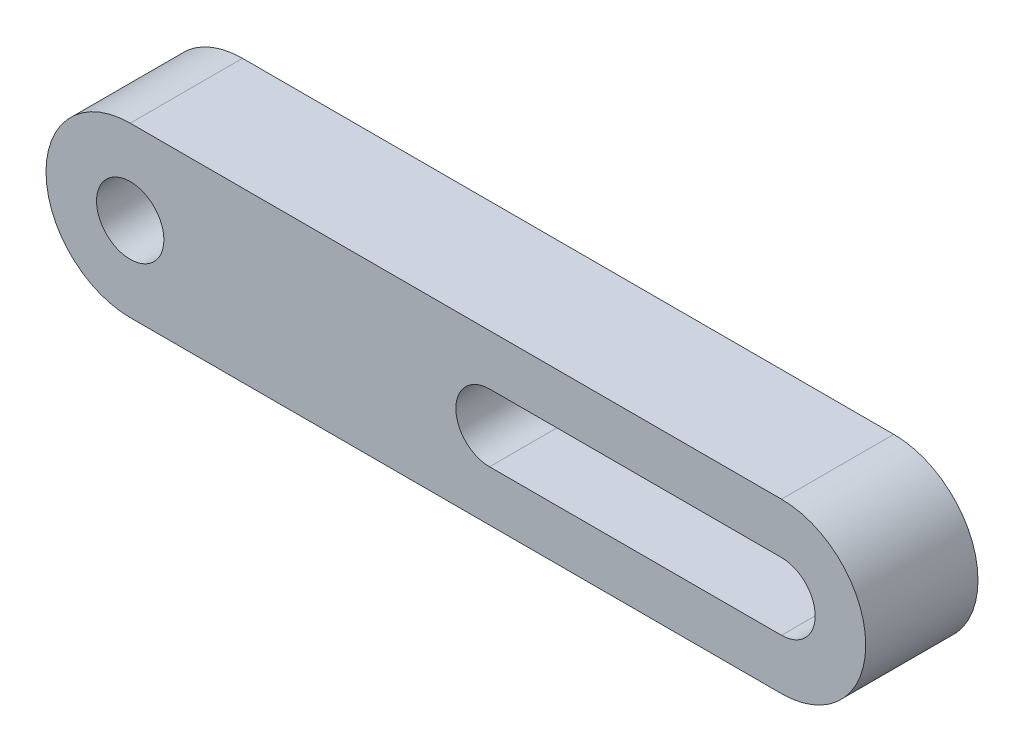
SolidWorks part; units mm, degrees
ref_plane "Alzado" through (0, 0, 0) normal (0, 0, 1) x (1, 0, 0)
ref_plane "Planta" through (0, 0, 0) normal (0, 1, 0) x (1, 0, 0)
ref_plane "Vista lateral" through (0, 0, 0) normal (1, 0, 0) x (0, 0, -1)
sketch "Croquis1" plane through (0, 0, 0) normal (0, 0, 1) x (1, 0, 0)
  line L0 (0, 0) -> (29, 0) construction
  line L1 (0, 3.75) -> (29, 3.75)
  line L2 (0, -3.75) -> (29, -3.75)
  line L3 (29, 0) -> (16, 0) construction
  line L4 (29, -1.5) -> (16, -1.5)
  line L5 (29, 1.5) -> (16, 1.5)
  line L6 (16, 1.5) -> (16, -1.5) construction
  arc A0 (0, 3.75) -> (0, -3.75) centre (0, 0) ccw
  arc A1 (29, -3.75) -> (29, 3.75) centre (29, 0) ccw
  circle A2 centre (0, 0) radius 1.5
  arc A4 (29, -1.5) -> (29, 1.5) centre (29, 0) ccw
  arc A5 (16, 1.5) -> (16, -1.5) centre (16, 0) ccw
  point P3 (14.5, 0)
  point P12 (22.5, 0)
  dimension "D3" = 3
  dimension "D4" = 1.5
  dimension "D1" = 13
  dimension "D2" = 7.5
  dimension "D5" = 16
extrude "Saliente-Extruir1" add sketch "Croquis1" along normal blind 5
ref_plane "Plano1" through (0, 0, 2.5) normal (0, 0, 1) x (1, 0, 0)
sketch "Croquis3" plane through (0, 0, 2.5) normal (0, 0, 1) x (1, 0, 0)
  line L0 (16, 1.5) -> (16, -1.5) construction
  line L1 (29, 1.5) -> (29, -1.5) construction
  line L2 (16, 0) -> (29, 0)
